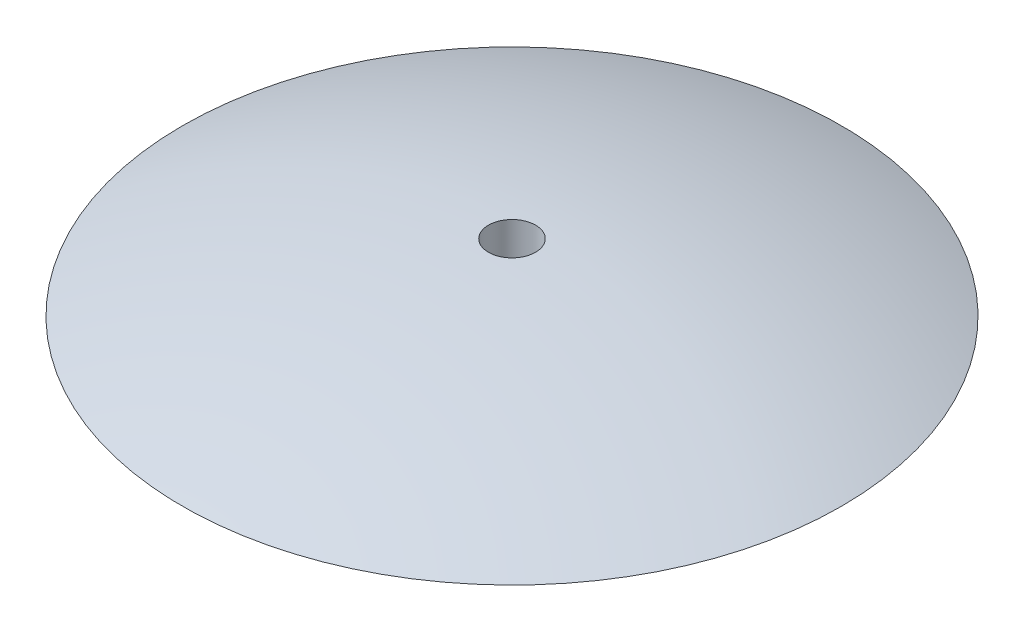
SolidWorks part; units mm, degrees
ref_plane "前基準面" through (0, 0, 0) normal (0, 0, 1) x (1, 0, 0)
ref_plane "上基準面" through (0, 0, 0) normal (0, 1, 0) x (1, 0, 0)
ref_plane "右基準面" through (0, 0, 0) normal (1, 0, 0) x (0, 0, -1)
sketch "草圖1" plane through (0, 0, 0) normal (0, 0, 1) x (1, 0, 0)
  line L0 (48.9898, 115) -> (0, 115)
  line L1 (0, 115) -> (0, 125)
  line L2 (0, 156.2215) -> (0, -14.1654) construction
  arc A0 (48.9898, 115) -> (0, 125) centre (0, 0) ccw
  dimension "D1" = 125
  dimension "D2" = 10
revolve "旋轉1" add sketch "草圖1" angle 360 about L2
sketch "草圖2" plane through (0, 115, 0) normal (0, -1, 0) x (1, 0, 0)
  circle A0 centre (0, 0) radius 3.5
  dimension "D1" = 7
extrude "除料-伸長2" cut sketch "草圖2" against normal through all
